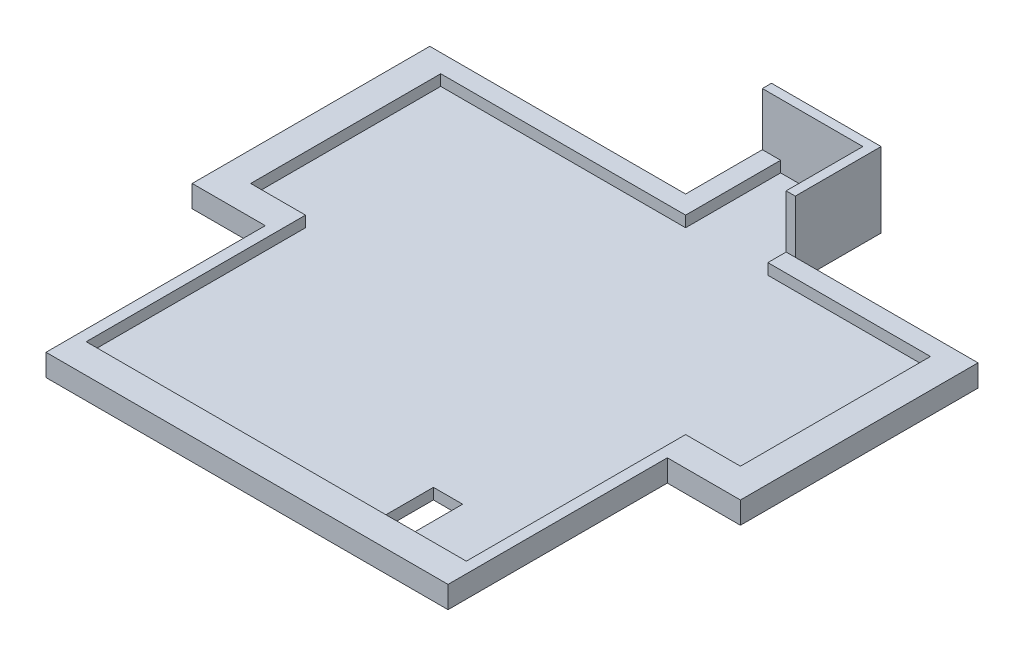
SolidWorks part; units mm, degrees
ref_plane "Alzado" through (0, 0, 0) normal (0, 0, 1) x (1, 0, 0)
ref_plane "Planta" through (0, 0, 0) normal (0, 1, 0) x (1, 0, 0)
ref_plane "Vista lateral" through (0, 0, 0) normal (1, 0, 0) x (0, 0, -1)
sketch "Croquis1" plane through (0, 0, 0) normal (0, 1, 0) x (1, 0, 0)
  line L1 (-75, -74.25) -> (75, -74.25)
  line L2 (-75, -74.25) -> (-75, 74.25)
  line L3 (-75, 74.25) -> (75, 74.25)
  line L4 (75, -74.25) -> (75, 74.25)
  line L5 (-75, -74.25) -> (75, 74.25) construction
  line L6 (-75, 74.25) -> (75, -74.25) construction
  point P0 (0, 0)
  dimension "150" = 150
  dimension "D2" = 148.5
extrude "Saliente-Extruir1" add sketch "Croquis1" along normal blind 6
sketch "Croquis2" plane through (0, 6, 0) normal (0, 1, 0) x (1, 0, 0)
  line L0 (-75, 50.75) -> (-75, -14.25)
  line L1 (-75, 74.25) -> (-75, -74.25) construction
  line L2 (-75, -14.25) -> (-55, -14.25)
  line L3 (-55, -14.25) -> (-55, -74.25)
  line L4 (-75, -74.25) -> (75, -74.25) construction
  line L5 (-55, -74.25) -> (55, -74.25)
  line L6 (55, -74.25) -> (55, -14.25)
  line L7 (55, -14.25) -> (75, -14.25)
  line L8 (75, -74.25) -> (75, 74.25) construction
  line L9 (75, -14.25) -> (75, 50.75)
  line L11 (-75, 50.75) -> (-5, 50.75)
  line L12 (-5, 50.75) -> (-5, 74.25)
  line L13 (75, 74.25) -> (-75, 74.25) construction
  line L14 (-5, 74.25) -> (25, 74.25)
  line L15 (25, 74.25) -> (25, 50.75)
  line L16 (25, 50.75) -> (75, 50.75)
  line L18 (-75, 50.75) -> (-5, 50.75)
  line L19 (-75, 50.75) -> (-75, 74.25)
  line L20 (-75, 74.25) -> (-5, 74.25)
  line L21 (-5, 50.75) -> (-5, 74.25)
  line L22 (25, 50.75) -> (75, 50.75)
  line L23 (25, 50.75) -> (25, 74.25)
  line L24 (25, 74.25) -> (75, 74.25)
  line L25 (75, 50.75) -> (75, 74.25)
  line L26 (55, -14.25) -> (75, -14.25)
  line L27 (55, -14.25) -> (55, -74.25)
  line L28 (55, -74.25) -> (75, -74.25)
  line L29 (75, -14.25) -> (75, -74.25)
  line L30 (-55, -14.25) -> (-75, -14.25)
  line L31 (-55, -14.25) -> (-55, -74.25)
  line L32 (-55, -74.25) -> (-75, -74.25)
  line L33 (-75, -14.25) -> (-75, -74.25)
  line M14 (75, -74.25) -> (75, 74.25)
  line M15 (75, 74.25) -> (-75, 74.25)
  line M16 (-75, 74.25) -> (-75, -74.25)
  line M17 (-75, -74.25) -> (75, -74.25)
  dimension "D1" = 20
  dimension "D2" = 20
  dimension "D3" = 65
  dimension "D4" = 65
  dimension "D5" = 60
  dimension "D6" = 50
  dimension "D7" = 70
extrude "Cortar-Extruir2" cut sketch "Croquis2" against normal blind 8 contours L15 L16 M14 M15 | L11 L12 M15 M16 | L3 L2 M16 M17 | L7 L6 M17 M14
sketch "Croquis3" plane through (0, 6, 0) normal (0, 1, 0) x (1, 0, 0)
  line L24 (47, -6.25) -> (67, -6.25)
  line L25 (67, -6.25) -> (67, 42.75)
  line L26 (67, 42.75) -> (17, 42.75)
  line L27 (17, 42.75) -> (17, 66.25)
  line L28 (17, 66.25) -> (3, 66.25)
  line L29 (3, 66.25) -> (3, 42.75)
  line L30 (3, 42.75) -> (-67, 42.75)
  line L31 (-67, 42.75) -> (-67, -6.25)
  line L32 (-67, -6.25) -> (-47, -6.25)
  line L33 (-47, -6.25) -> (-47, -66.25)
  line L34 (-47, -66.25) -> (47, -66.25)
  line L35 (47, -66.25) -> (47, -6.25)
  line L36 (47, -6.25) -> (67, -6.25)
  line L37 (67, -6.25) -> (67, 42.75)
  line L38 (67, 42.75) -> (17, 42.75)
  line L39 (17, 42.75) -> (17, 66.25)
  line L40 (17, 66.25) -> (3, 66.25)
  line L41 (3, 66.25) -> (3, 42.75)
  line L42 (3, 42.75) -> (-67, 42.75)
  line L43 (-67, 42.75) -> (-67, -6.25)
  line L44 (-67, -6.25) -> (-47, -6.25)
  line L45 (-47, -6.25) -> (-47, -66.25)
  line L46 (-47, -66.25) -> (47, -66.25)
  line L47 (47, -66.25) -> (47, -6.25)
  dimension "D1" = 8
extrude "Cortar-Extruir3" cut sketch "Croquis3" against normal blind 3
sketch "Croquis4" plane through (0, 6, 0) normal (0, 1, 0) x (1, 0, 0)
  line L0 (25, 50.75) -> (75, 50.75) construction
  line L1 (-67, 42.75) -> (67, 42.75)
  line L2 (-67, 42.75) -> (-67, 45.75)
  line L3 (-67, 45.75) -> (67, 45.75)
  line L4 (67, 42.75) -> (67, 45.75)
  line L5 (-67, -6.25) -> (-47, -6.25) construction
  line L6 (-47, -66.25) -> (-52, -66.25)
  line L7 (-47, -66.25) -> (-47, -6.25)
  line L8 (-47, -6.25) -> (-52, -6.25)
  line L9 (-52, -66.25) -> (-52, -6.25)
  line L10 (47, -6.25) -> (52, -6.25)
  line L11 (0, 0) -> (0, -19.962) construction
  line L12 (-55, -14.25) -> (-55, -74.25) construction
  line L13 (52, -66.25) -> (52, -6.25)
  line L14 (47, -66.25) -> (52, -66.25)
  line L15 (47, -66.25) -> (47, -6.25)
  line L17 (25, 74.25) -> (-5, 74.25) construction
  line L18 (0, 66.25) -> (22.5, 66.25)
  line L19 (0, 66.25) -> (0, 71.75)
  line L20 (0, 71.75) -> (22.5, 71.75)
  line L21 (22.5, 66.25) -> (22.5, 71.75)
  line L22 (17, 66.25) -> (3, 66.25) construction
  line L23 (-5, 50.75) -> (-5, 74.25) construction
  line L24 (25, 74.25) -> (25, 50.75) construction
  point P46 (0, 0)
  dimension "D1" = 5
  dimension "D2" = 3
  dimension "D3" = 2.5
  dimension "D4" = 5
  dimension "D5" = 2.5
extrude "Cortar-Extruir4" cut sketch "Croquis4" against normal blind 3
sketch "Croquis5" plane through (0, 6, 0) normal (0, 1, 0) x (1, 0, 0)
  line L0 (-5, 50.75) -> (-5, 74.25) construction
  line L1 (3, 66.25) -> (0, 66.25)
  line L2 (3, 66.25) -> (3, 45.75)
  line L3 (3, 45.75) -> (0, 45.75)
  line L4 (0, 66.25) -> (0, 45.75)
  line L5 (17, 66.25) -> (22.5, 66.25)
  line L6 (17, 66.25) -> (17, 45.75)
  line L7 (17, 45.75) -> (22.5, 45.75)
  line L8 (22.5, 66.25) -> (22.5, 45.75)
  line L9 (25, 74.25) -> (25, 50.75) construction
  line L10 (3, 45.75) -> (-67, 45.75) construction
  line L11 (67, 45.75) -> (17, 45.75) construction
  dimension "D3" = 5
  dimension "D4" = 2.5
extrude "Cortar-Extruir5" cut sketch "Croquis5" against normal blind 3
sketch "Croquis7" plane through (0, 6, 0) normal (0, 1, 0) x (1, 0, 0)
  line L0 (25, 50.75) -> (25, 74.25)
  line L1 (25, 74.25) -> (-5, 74.25)
  line L2 (-5, 74.25) -> (-5, 71.75)
  line L3 (-5, 50.75) -> (-5, 74.25) construction
  line L4 (-5, 71.75) -> (22.5, 71.75)
  line L5 (22.5, 71.75) -> (22.5, 50.75)
  line L6 (22.5, 45.75) -> (22.5, 71.75) construction
  line L7 (22.5, 50.75) -> (25, 50.75)
  line L8 (22.5, 71.75) -> (0, 71.75) construction
extrude "Saliente-Extruir3" add sketch "Croquis7" along normal blind 14.5
sketch "Croquis8" plane through (0, 6, 0) normal (0, 1, 0) x (1, 0, 0)
  line L0 (-75, 50.75) -> (-75, -14.25) construction
  line L5 (-74, 11.75) -> (-68, 11.75)
  line L6 (-74, 11.75) -> (-74, 24.75)
  line L7 (-74, 24.75) -> (-68, 24.75)
  line L8 (-68, 11.75) -> (-68, 24.75)
  line L9 (-74, 11.75) -> (-68, 24.75) construction
  line L10 (-74, 24.75) -> (-68, 11.75) construction
  line L11 (-75, 50.75) -> (-75, -14.25) construction
  line L12 (0, 0) -> (0, 15.2902) construction
  line L13 (74, 24.75) -> (68, 24.75)
  line L14 (68, 11.75) -> (68, 24.75)
  line L15 (74, 11.75) -> (68, 11.75)
  line L16 (74, 11.75) -> (74, 24.75)
  line L17 (-52, -66.25) -> (52, -66.25) construction
  line L18 (-6.5, -73.25) -> (6.5, -73.25)
  line L19 (-6.5, -73.25) -> (-6.5, -67.25)
  line L20 (-6.5, -67.25) -> (6.5, -67.25)
  line L21 (6.5, -73.25) -> (6.5, -67.25)
  line L22 (-6.5, -73.25) -> (6.5, -67.25) construction
  line L23 (-6.5, -67.25) -> (6.5, -73.25) construction
  point P0 (-71, 18.25)
  point P12 (-75, 18.25)
  point P19 (0, -70.25)
  point P26 (0, 0)
  dimension "D1" = 6
  dimension "D2" = 4
  dimension "D3" = 13
  dimension "D4" = 1
  dimension "D5" = 13
  dimension "D6" = 6
extrude "Cortar-Extruir6" cut sketch "Croquis8" against normal blind 3
sketch "Croquis9" plane through (0, 3, 0) normal (0, 1, 0) x (1, 0, 0)
  line L0 (55, -74.25) -> (55, -14.25) construction
  line L1 (27, -66.25) -> (35, -66.25)
  line L2 (27, -66.25) -> (27, -50.25)
  line L3 (27, -50.25) -> (35, -50.25)
  line L4 (35, -66.25) -> (35, -50.25)
  line L5 (27, -66.25) -> (35, -50.25) construction
  line L6 (27, -50.25) -> (35, -66.25) construction
  line L8 (-52, -66.25) -> (52, -66.25) construction
  point P0 (31, -58.25)
  point P5 (27, -58.25)
  dimension "D1" = 28
  dimension "D2" = 8
  dimension "D3" = 16
extrude "Cortar-Extruir7" cut sketch "Croquis9" against normal through all
sketch "Croquis10" plane through (0, 6, 0) normal (0, 1, 0) x (1, 0, 0)
  line L23 (25, 50.75) -> (22.5, 50.75)
  line L24 (22.5, 50.75) -> (22.5, 45.75)
  line L25 (22.5, 45.75) -> (67, 45.75)
  line L26 (67, 45.75) -> (67, -6.25)
  line L27 (67, -6.25) -> (52, -6.25)
  line L28 (52, -6.25) -> (52, -66.25)
  line L29 (52, -66.25) -> (-52, -66.25)
  line L30 (-52, -66.25) -> (-52, -6.25)
  line L31 (-52, -6.25) -> (-67, -6.25)
  line L32 (-67, -6.25) -> (-67, 45.75)
  line L33 (-67, 45.75) -> (0, 45.75)
  line L34 (0, 45.75) -> (0, 71.75)
  line L35 (0, 71.75) -> (-5, 71.75)
  line L36 (-5, 71.75) -> (-5, 50.75)
  line L37 (-5, 50.75) -> (-75, 50.75)
  line L38 (-75, 50.75) -> (-75, -14.25)
  line L39 (-75, -14.25) -> (-55, -14.25)
  line L40 (-55, -14.25) -> (-55, -74.25)
  line L41 (-55, -74.25) -> (55, -74.25)
  line L42 (55, -74.25) -> (55, -14.25)
  line L43 (55, -14.25) -> (75, -14.25)
  line L44 (75, -14.25) -> (75, 50.75)
  line L45 (75, 50.75) -> (25, 50.75)
  line L46 (25, 50.75) -> (22.5, 50.75)
  line L47 (22.5, 50.75) -> (22.5, 45.75)
  line L48 (22.5, 45.75) -> (67, 45.75)
  line L49 (67, 45.75) -> (67, -6.25)
  line L50 (67, -6.25) -> (52, -6.25)
  line L51 (52, -6.25) -> (52, -66.25)
  line L52 (52, -66.25) -> (-52, -66.25)
  line L53 (-52, -66.25) -> (-52, -6.25)
  line L54 (-52, -6.25) -> (-67, -6.25)
  line L55 (-67, -6.25) -> (-67, 45.75)
  line L56 (-67, 45.75) -> (0, 45.75)
  line L57 (0, 45.75) -> (0, 71.75)
  line L58 (0, 71.75) -> (-5, 71.75)
  line L59 (-5, 71.75) -> (-5, 50.75)
  line L60 (-5, 50.75) -> (-75, 50.75)
  line L61 (-75, 50.75) -> (-75, -14.25)
  line L62 (-75, -14.25) -> (-55, -14.25)
  line L63 (-55, -14.25) -> (-55, -74.25)
  line L64 (-55, -74.25) -> (55, -74.25)
  line L65 (55, -74.25) -> (55, -14.25)
  line L66 (55, -14.25) -> (75, -14.25)
  line L67 (75, -14.25) -> (75, 50.75)
  line L68 (75, 50.75) -> (25, 50.75)
  dimension "D1" = 0
extrude "Saliente-Extruir4" add sketch "Croquis10" against normal blind 1
